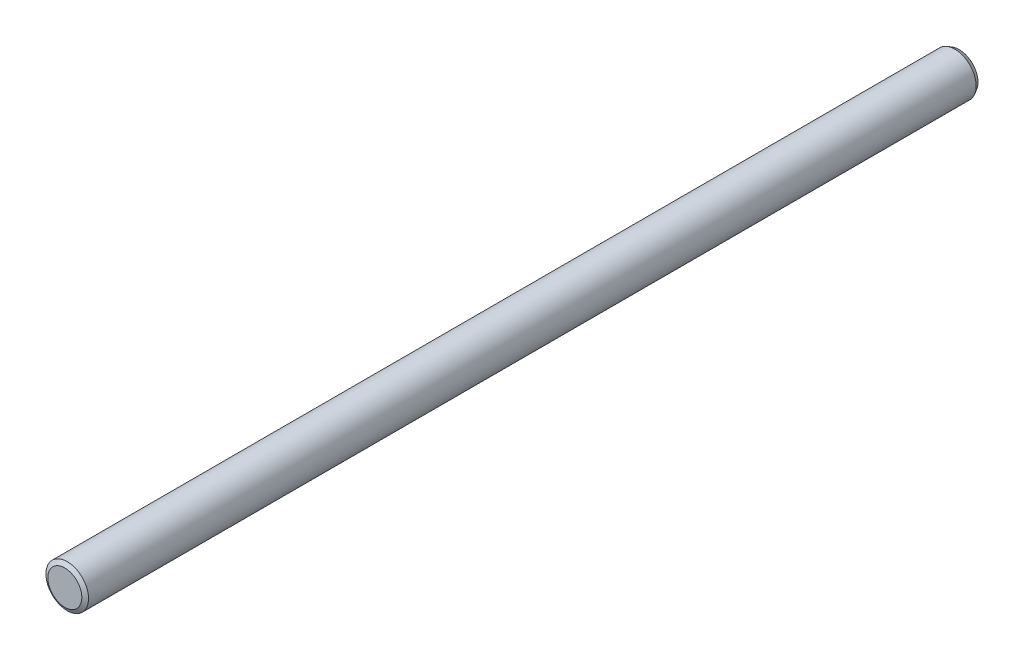
SolidWorks part; units mm, degrees
material "Liga de aço fundido"
ref_plane "Plano frontal" through (0, 0, 0) normal (0, 0, 1) x (1, 0, 0)
ref_plane "Plano superior" through (0, 0, 0) normal (0, 1, 0) x (1, 0, 0)
ref_plane "Plano direito" through (0, 0, 0) normal (1, 0, 0) x (0, 0, -1)
sketch "Esboço1" plane through (0, 0, 0) normal (0, 0, 1) x (1, 0, 0)
  circle A1 centre (0.25, 20.5091) radius 0.25
  dimension "D1" = 0.5
extrude "Ressalto-extrusão1" add sketch "Esboço1" along normal blind 10.5
chamfer "Chanfro1" distance 0.05 angle 30 2 edges at (0.5, 20.5091, 10.5) (0.5, 20.5091, 0)
